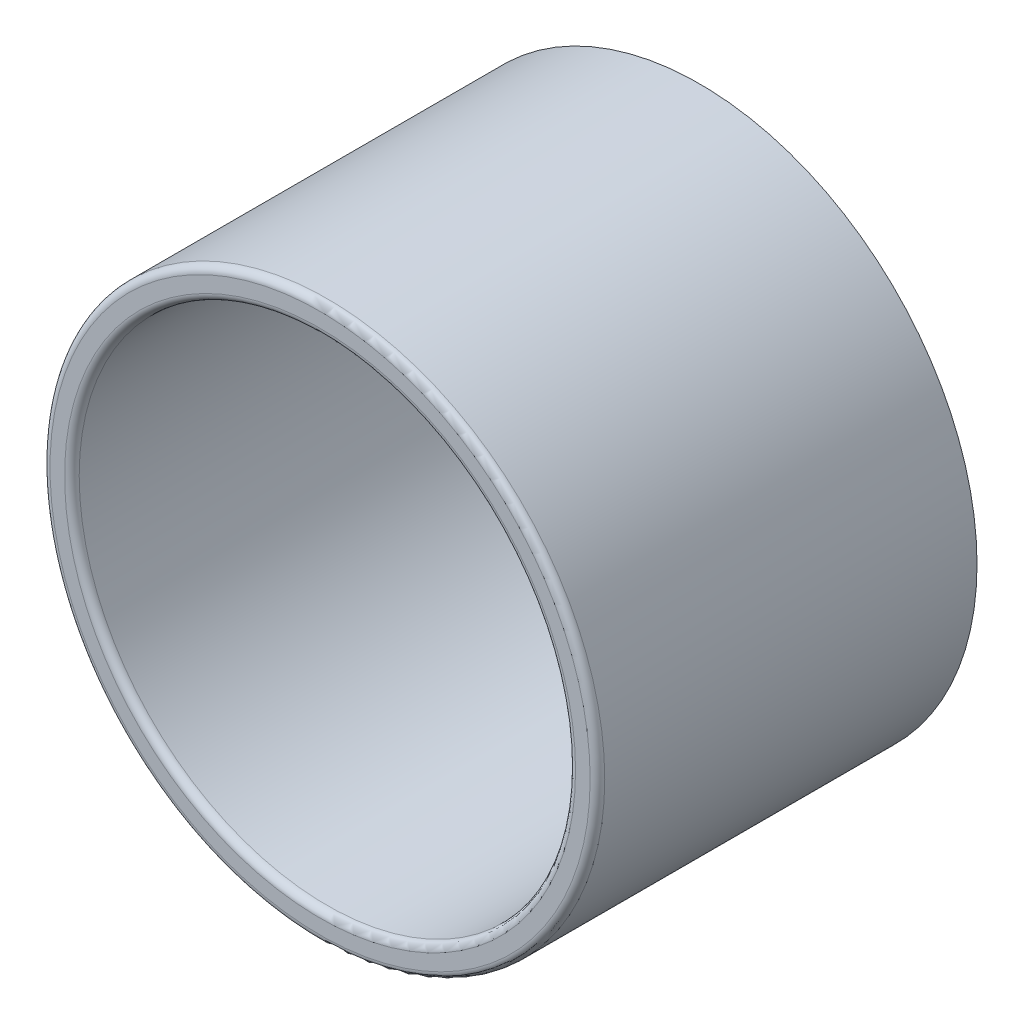
SolidWorks part; units mm, degrees
material "moto_yellow"
ref_plane "Front Plane" through (0, 0, 0) normal (0, 0, 1) x (1, 0, 0)
ref_plane "Top Plane" through (0, 0, 0) normal (0, 1, 0) x (1, 0, 0)
ref_plane "Right Plane" through (0, 0, 0) normal (1, 0, 0) x (0, 0, -1)
sketch "Sketch1" plane through (0, 0, 0) normal (0, 0, 1) x (1, 0, 0)
  circle A0 centre (0, 0) radius 19
  circle A1 centre (0, 0) radius 17
  dimension "D1" = 38
  dimension "D2" = 2
extrude "Boss-Extrude1" add sketch "Sketch1" against normal blind 26
fillet "Fillet1" radius 0.5 2 edges at (17, 0, 0) (19, 0, 0)
